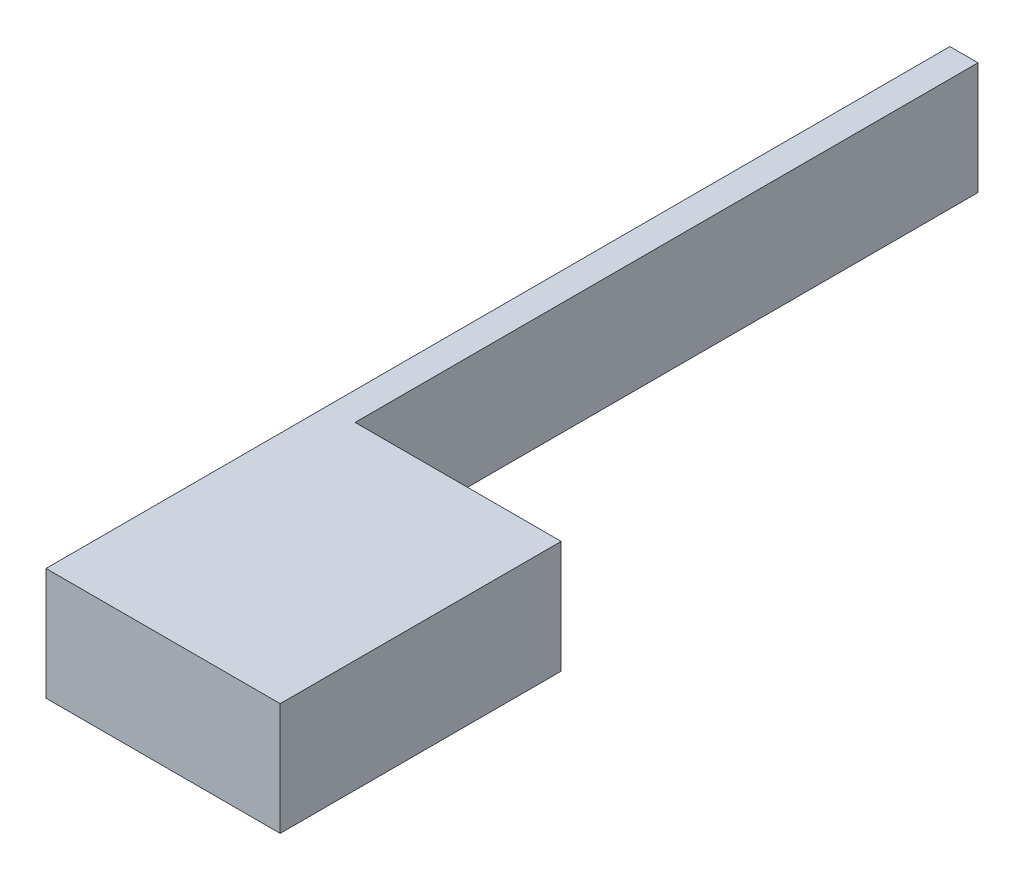
SolidWorks part; units mm, degrees
material "Perspex (TM) GS Acrylic Cast Sheet"
ref_plane "Front Plane" through (0, 0, 0) normal (0, 0, 1) x (1, 0, 0)
ref_plane "Top Plane" through (0, 0, 0) normal (0, 1, 0) x (1, 0, 0)
ref_plane "Right Plane" through (0, 0, 0) normal (1, 0, 0) x (0, 0, -1)
sketch "Sketch1" plane through (0, 0, 0) normal (1, 0, 0) x (0, 0, -1)
  line L1 (0, 0) -> (96.5, 0)
  line L2 (0, 0) -> (0, 12)
  line L3 (0, 12) -> (96.5, 12)
  line L4 (96.5, 0) -> (96.5, 12)
  dimension "D1" = 96.5
  dimension "D2" = 12
extrude "Boss-Extrude1" add sketch "Sketch1" along normal blind 3
sketch "Sketch2" plane through (3, 0, 0) normal (1, 0, 0) x (0, 0, -1)
  line L0 (0, 0) -> (96.5, 0) construction
  line L1 (0, 12) -> (30, 12)
  line L2 (0, 12) -> (0, 0)
  line L3 (0, 0) -> (30, 0)
  line L4 (30, 12) -> (30, 0)
  dimension "D1" = 30
extrude "Boss-Extrude2" add sketch "Sketch2" along normal blind 22
